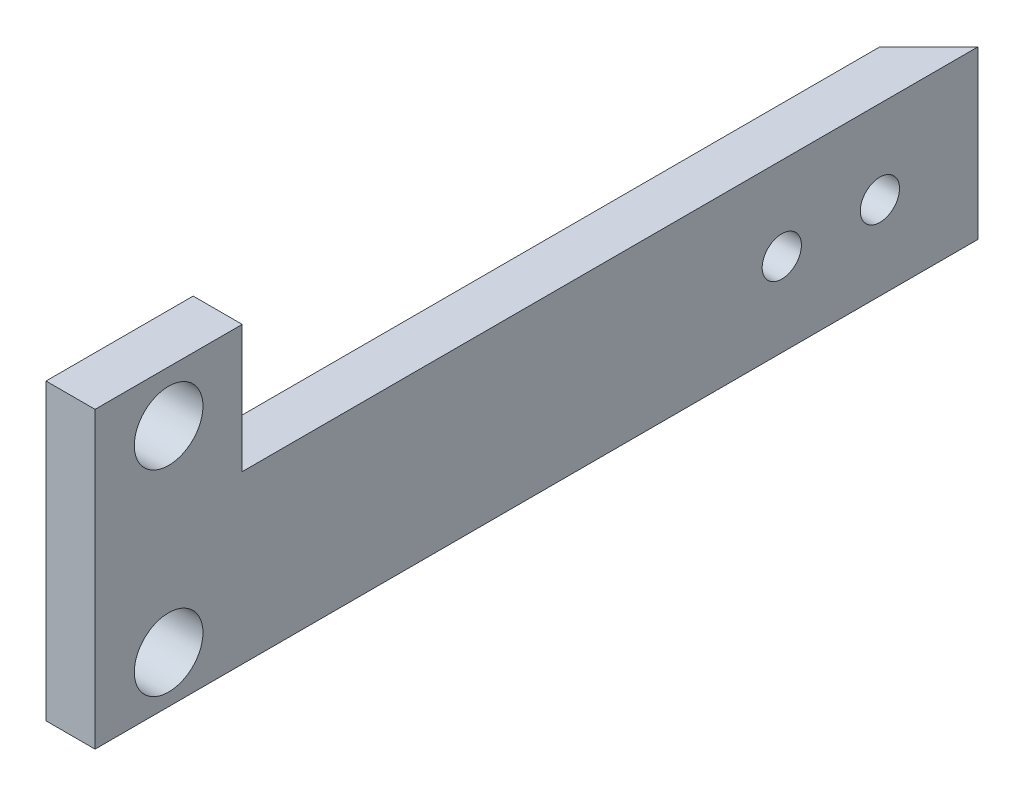
SolidWorks part; units mm, degrees
ref_plane "Front Plane" through (0, 0, 0) normal (0, 0, 1) x (1, 0, 0)
ref_plane "Top Plane" through (0, 0, 0) normal (0, 1, 0) x (1, 0, 0)
ref_plane "Right Plane" through (0, 0, 0) normal (1, 0, 0) x (0, 0, -1)
sketch "Croquis1" plane through (0, 0, 0) normal (0, 0, 1) x (1, 0, 0)
  line L1 (-2.5, -15) -> (2.5, -15)
  line L2 (-2.5, -15) -> (-2.5, 15)
  line L3 (-2.5, 15) -> (2.5, 15)
  line L4 (2.5, -15) -> (2.5, 15)
  line L5 (-2.5, -15) -> (2.5, 15) construction
  line L6 (-2.5, 15) -> (2.5, -15) construction
  point P0 (0, 0)
  dimension "D1" = 30
  dimension "D2" = 5
extrude "Saliente-Extruir1" add sketch "Croquis1" along normal blind 15
sketch "Croquis2" plane through (2.5, 0, 0) normal (1, 0, 0) x (0, 0, -1)
  line L0 (-15, 15) -> (0, 15) construction
  circle A0 centre (-7.5, 9.7951) radius 3.5
  circle A1 centre (-7.5, -10.2049) radius 3.5
  point P7 (-7.5, 15)
  dimension "D1" = 7
  dimension "D2" = 7
  dimension "D3" = 20
extrude "Cortar-Extruir1" cut sketch "Croquis2" against normal blind 15
sketch "Croquis3" plane through (0, 0, 0) normal (0, 0, -1) x (-1, 0, 0)
  line L1 (-2.5, 2) -> (2.5, 2)
  line L2 (-2.5, 2) -> (-2.5, -15)
  line L3 (-2.5, -15) -> (2.5, -15)
  line L4 (2.5, 2) -> (2.5, -15)
  line L5 (-2.5, 2) -> (2.5, -15) construction
  line L6 (-2.5, -15) -> (2.5, 2) construction
  point P0 (0, -6.5)
  dimension "D1" = 17
  dimension "D2" = 5
extrude "Saliente-Extruir2" add sketch "Croquis3" along normal blind 80
sketch "Croquis5" plane through (2.5, 0, 0) normal (1, 0, 0) x (0, 0, -1)
  line L0 (80, 2) -> (80, -15) construction
  line L1 (80, -15) -> (80, 2) construction
  circle A0 centre (65, -6.5) radius 2
  circle A1 centre (55, -6.5) radius 2
  point P4 (0, 0)
  point P9 (80, -6.5)
  dimension "D1" = 4
  dimension "D2" = 4
  dimension "D3" = 10
  dimension "D4" = 15
extrude "Cortar-Extruir3" cut sketch "Croquis5" against normal blind 75
sketch "Croquis6" plane through (0, 2, 0) normal (0, 1, 0) x (1, 0, 0)
  line L13 (2.5, 75) -> (2.5, 70)
  line L14 (2.5, 80) -> (2.5, 0) construction
  line L15 (2.5, 70) -> (-2.5, 70)
  line L16 (-2.5, 80) -> (-2.5, 0) construction
  line L17 (-2.5, 70) -> (2.5, 75)
  line L18 (-2.5, 70) -> (-2.5, 80)
  line L19 (-2.5, 80) -> (2.5, 80)
  line L20 (2.5, 80) -> (2.5, 75)
  dimension "D1" = 5
  dimension "D2" = 5
extrude "Cortar-Extruir4" cut sketch "Croquis6" against normal blind 30
